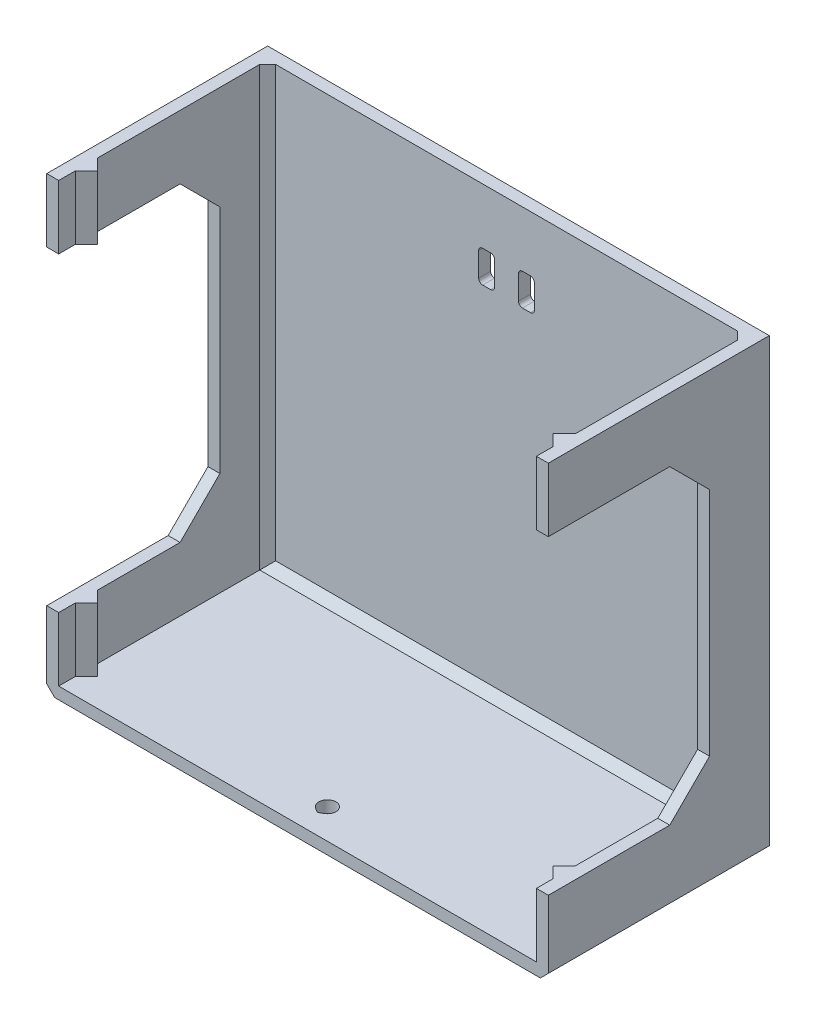
SolidWorks part; units mm, degrees
ref_plane "Front Plane" through (0, 0, 0) normal (0, 0, 1) x (1, 0, 0)
ref_plane "Top Plane" through (0, 0, 0) normal (0, 1, 0) x (1, 0, 0)
ref_plane "Right Plane" through (0, 0, 0) normal (1, 0, 0) x (0, 0, -1)
sketch "Sketch1" plane through (0, 0, 0) normal (0, 0, 1) x (1, 0, 0)
  line L0 (-60, 52) -> (-63, 52) construction
  line L1 (60, -52) -> (-60, -52) construction
  line L2 (60, -52) -> (60, 52) construction
  line L3 (60, 52) -> (-60, 52) construction
  line L4 (-60, -52) -> (-60, 52) construction
  line L5 (60, -52) -> (-60, 52) construction
  line L6 (60, 52) -> (-60, -52) construction
  line L7 (63, -55) -> (-63, -55)
  line L8 (63, -55) -> (63, 55)
  line L9 (63, 55) -> (-63, 55)
  line L10 (-63, -55) -> (-63, 55)
  line L11 (63, -55) -> (-63, 55) construction
  line L12 (63, 55) -> (-63, -55) construction
  line L13 (-60, 52) -> (-60, 55) construction
  point P0 (0, 0)
  point P6 (0, 0)
  dimension "D1" = 120
  dimension "D2" = 104
  dimension "D3" = 3
extrude "Boss-Extrude1" add sketch "Sketch1" along normal blind 3
sketch "Sketch2" plane through (-63, 0, 0) normal (-1, 0, 0) x (0, 0, 1)
  line L0 (53, 39) -> (53, -39) construction
  line L1 (3, 55) -> (53, 55)
  line L2 (3, 55) -> (3, 39)
  line L3 (3, 39) -> (53, 39)
  line L4 (53, 55) -> (53, 39)
  line L5 (3, -55) -> (53, -55)
  line L6 (3, -55) -> (3, -39)
  line L7 (3, -39) -> (53, -39)
  line L8 (53, -55) -> (53, -39)
  dimension "D1" = 50
  dimension "D2" = 16
extrude "Boss-Extrude2" add sketch "Sketch2" against normal blind 3
sketch "Sketch3" plane through (0, -55, 0) normal (0, -1, 0) x (1, 0, 0)
  line L0 (-60, 45.5) -> (-57, 48.5)
  line L1 (-60, 3) -> (-60, 53) construction
  line L2 (-57, 48.5) -> (-60, 51.5)
  line L3 (-60, 51.5) -> (-60, 45.5)
  line L4 (-57, 48.5) -> (-60, 48.5) construction
  line L5 (-60, 53) -> (-60, 44) construction
  point P6 (-60, 48.5)
  dimension "D1" = 6
  dimension "D2" = 9
extrude "Boss-Extrude3" add sketch "Sketch3" against normal up to surface (16 mm away) up to face at (-61.5, -39, 28)
sketch "Sketch4" plane through (0, 55, 0) normal (0, 1, 0) x (1, 0, 0)
  line L0 (-60, -51.5) -> (-57, -48.5)
  line L1 (-60, -53) -> (-60, -3) construction
  line L2 (-57, -48.5) -> (-60, -45.5)
  line L3 (-60, -45.5) -> (-60, -51.5)
extrude "Boss-Extrude4" add sketch "Sketch4" against normal up to surface (16 mm away) up to face at (-61.5, 39, 28)
mirror "Mirror1" about plane through (0, 0, 0) normal (1, 0, 0) of "Boss-Extrude2", "Boss-Extrude3", "Boss-Extrude4"
sketch "Sketch5" plane through (0, -55, 0) normal (0, -1, 0) x (1, 0, 0)
  line L1 (-63, 53) -> (63, 53)
  line L2 (-63, 53) -> (-63, 0)
  line L3 (-63, 0) -> (63, 0)
  line L4 (63, 53) -> (63, 0)
extrude "Boss-Extrude5" add sketch "Sketch5" along normal blind 3
sketch "Sketch7" plane through (0, 0, 3) normal (0, 0, 1) x (1, 0, 0)
  line L0 (-60, 39) -> (-63, 39) construction
  line L1 (-63, 39) -> (-60, 39)
  line L2 (-63, 39) -> (-63, -39)
  line L3 (-63, -39) -> (-60, -39)
  line L4 (-60, 39) -> (-60, -39)
  line L5 (63, 39) -> (60, 39)
  line L6 (63, 39) -> (63, -39)
  line L7 (63, -39) -> (60, -39)
  line L8 (60, 39) -> (60, -39)
  line L9 (-63, 39) -> (-63, -39) construction
  point P11 (-60, 39)
  point P15 (-63, 39)
extrude "Boss-Extrude6" add sketch "Sketch7" along normal blind 12
ref_plane "Plane1" through (0, 0, 48.5) normal (0, 0, 1) x (1, 0, 0)
sketch "Sketch8" plane through (0, -58, 0) normal (0, -1, 0) x (1, 0, 0)
  line L0 (0, 53) -> (0, 48) construction
  line L1 (63, 53) -> (-63, 53) construction
  circle A0 centre (0, 48) radius 2.15
  dimension "D1" = 4.3
  dimension "D2" = 5
extrude "Cut-Extrude1" cut sketch "Sketch8" against normal through all
sketch "Sketch9" plane through (0, -58, 0) normal (0, -1, 0) x (1, 0, 0)
  line L0 (-1.075, 49.862) -> (0, 50.4826)
  line L1 (0, 50.4826) -> (1.075, 49.862)
  line L2 (1.075, 49.862) -> (-1.075, 49.862)
  line L3 (0, 50.4826) -> (0, 49.862) construction
  circle A0 centre (0, 48) radius 2.15 construction
  point P6 (-1.744, 49.2574)
  point P7 (0, 49.5242)
  point P8 (0, 50.4017)
  dimension "D1" = 120
extrude "Cut-Extrude2" cut sketch "Sketch9" against normal through all
sketch "Sketch10" plane through (0, -55, 0) normal (0, 1, 0) x (1, 0, 0)
  line L0 (-60, -45.5) -> (-60, -45.7)
  line L1 (-60, -45.7) -> (-57.2, -48.5)
  line L2 (-57.2, -48.5) -> (-60, -51.3)
  line L3 (-60, -51.3) -> (-60, -51.5)
  line L4 (-60, -51.5) -> (-57, -48.5)
  line L5 (-57, -48.5) -> (-60, -45.5)
  line L7 (60, -45.7) -> (57.2, -48.5)
  line L8 (57.2, -48.5) -> (60, -51.3)
  line L9 (60, -51.3) -> (60, -51.5)
  line L10 (57, -48.5) -> (60, -51.5) construction
  line L11 (60, -51.5) -> (57, -48.5)
  line L12 (57, -48.5) -> (60, -45.5)
  line L13 (60, -45.5) -> (60, -45.7)
  line L14 (57.2, -48.5) -> (57, -48.5) construction
  line L15 (-57.2, -48.5) -> (-57, -48.5) construction
  point P19 (59.9842, -51.4842)
  dimension "D1" = 0.2
extrude "Cut-Extrude3" cut sketch "Sketch10" along normal through all
sketch "Sketch11" plane through (0, 0, 53) normal (0, 0, 1) x (1, 0, 0)
  line L0 (-63, -39) -> (-63, -58)
  line L1 (-63, 55) -> (-60, 55)
  line L2 (-63, 55) -> (-63, 39)
  line L3 (-63, 39) -> (-60, 39)
  line L4 (-60, 55) -> (-60, 39)
  line L5 (60, 55) -> (63, 55)
  line L6 (60, 55) -> (60, 39)
  line L7 (60, 39) -> (63, 39)
  line L8 (63, 55) -> (63, 39)
  line L9 (-63, -58) -> (63, -58)
  line L10 (63, -58) -> (63, -39)
  line L11 (63, -39) -> (60, -39)
  line L12 (60, -39) -> (60, -55)
  line L13 (60, -55) -> (-60, -55)
  line L14 (-60, -55) -> (-60, -39)
  line L15 (-60, -39) -> (-63, -39)
extrude "Boss-Extrude7" add sketch "Sketch11" along normal blind 2.5
chamfer "Chamfer1" distance 10 angle 45 4 edges at (-61.5, -39, 15) (-61.5, 39, 15) (61.5, 39, 15) (61.5, -39, 15)
chamfer "Chamfer2" distance 2 angle 45 3 edges at (-60, 0, 3) (0, -55, 3) (60, 0, 3)
sketch "Sketch12" plane through (0, 0, 3) normal (0, 0, 1) x (1, 0, 0)
  line L0 (0, 55) -> (0, 37) construction
  line L1 (58, 55) -> (-58, 55) construction
  line L2 (-5, 37) -> (5, 37) construction
  line L4 (-3, 33) -> (-7, 33)
  line L5 (-3, 33) -> (-3, 41)
  line L6 (-3, 41) -> (-7, 41)
  line L7 (-7, 33) -> (-7, 41)
  line L8 (-3, 33) -> (-7, 41) construction
  line L9 (-3, 41) -> (-7, 33) construction
  line L10 (7, 33) -> (3, 33)
  line L11 (7, 33) -> (7, 41)
  line L12 (7, 41) -> (3, 41)
  line L13 (3, 33) -> (3, 41)
  line L14 (7, 33) -> (3, 41) construction
  line L15 (7, 41) -> (3, 33) construction
  point P7 (0, 37)
  point P16 (4.6815, 41.9023)
  dimension "D1" = 18
  dimension "D2" = 10
  dimension "D3" = 4
  dimension "D4" = 8
extrude "Cut-Extrude4" cut sketch "Sketch12" against normal through all
fillet "Fillet1" radius 1 8 edges at (7, 33, 1.5) (3, 33, 1.5) (7, 41, 1.5) (3, 41, 1.5) (-3, 33, 1.5) (-7, 33, 1.5) (-7, 41, 1.5) (-3, 41, 1.5)
chamfer "Chamfer3" distance 2 angle 45 2 edges at (63, -58, 27.75) (-63, -58, 27.75)
